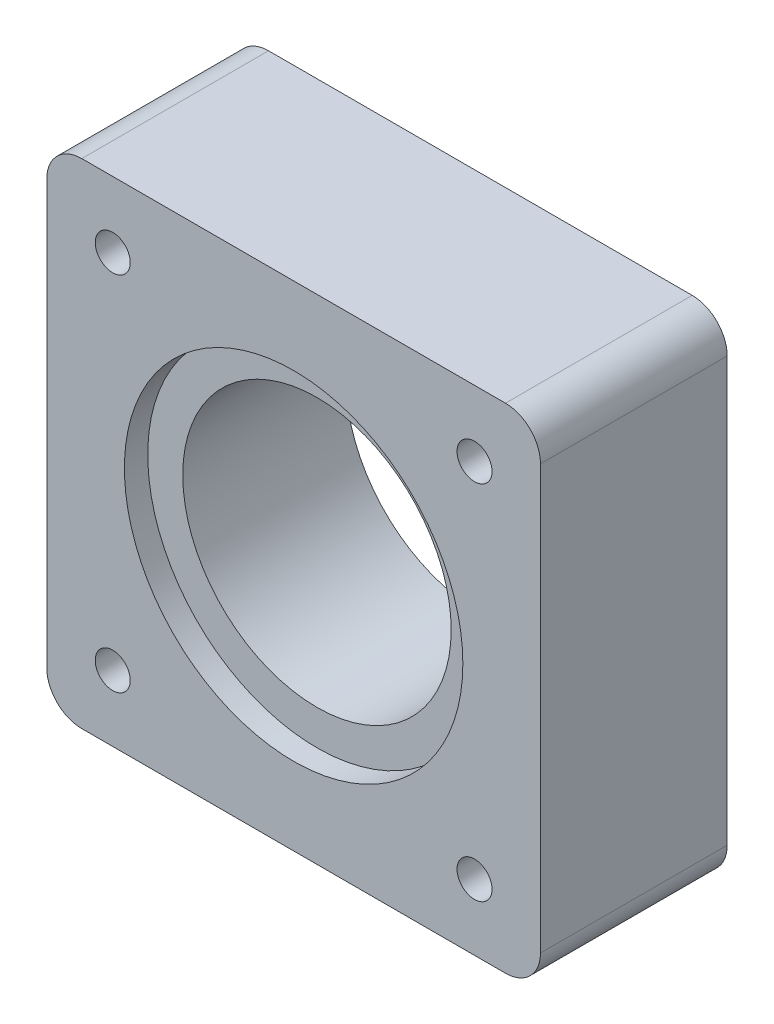
SolidWorks part; units mm, degrees
ref_plane "Plan de face" through (0, 0, 0) normal (0, 0, 1) x (1, 0, 0)
ref_plane "Plan de dessus" through (0, 0, 0) normal (0, 1, 0) x (1, 0, 0)
ref_plane "Plan de droite" through (0, 0, 0) normal (1, 0, 0) x (0, 0, -1)
sketch "Esquisse1" plane through (0, 0, 0) normal (0, 0, 1) x (1, 0, 0)
  line L1 (0, 0) -> (42.3, 0)
  line L2 (0, 0) -> (0, 42.3)
  line L3 (0, 42.3) -> (42.3, 42.3)
  line L4 (42.3, 0) -> (42.3, 42.3)
  dimension "D1" = 42.3
  dimension "D2" = 42.3
extrude "Boss.-Extru.1" add sketch "Esquisse1" along normal blind 16
sketch "Esquisse2" plane through (0, 0, 0) normal (0, 0, 1) x (1, 0, 0)
  line L0 (42.3, 0) -> (42.3, 42.3) construction
  line L2 (42.3, 42.3) -> (0, 42.3) construction
  line L3 (0, 42.3) -> (0, 0) construction
  line L5 (0, 0) -> (42.3, 0) construction
  circle A0 centre (36.65, 36.65) radius 1.5
  circle A1 centre (5.65, 36.65) radius 1.5
  circle A2 centre (5.65, 5.65) radius 1.5
  circle A3 centre (36.65, 5.65) radius 1.5
  dimension "D1" = 3
  dimension "D2" = 3
  dimension "D3" = 3
  dimension "D4" = 3
  dimension "D9" = 5.65
  dimension "D5" = 5.65
  dimension "D6" = 5.65
  dimension "D7" = 5.65
  dimension "D8" = 5.65
  dimension "D10" = 5.65
  dimension "D11" = 5.65
  dimension "D12" = 5.65
extrude "Enlèv. mat.-Extru.2" cut sketch "Esquisse2" along normal through all
fillet "Congé1" radius 3 2 edges at (0, 42.3, 8) (42.3, 42.3, 8)
fillet "Congé2" radius 3 2 edges at (42.3, 0, 8) (0, 0, 8)
sketch "Esquisse4" plane through (0, 0, 0) normal (0, 0, 1) x (1, 0, 0)
  line L0 (39.3, 42.3) -> (3, 42.3) construction
  line L1 (0, 39.3) -> (0, 3) construction
  circle A0 centre (21.15, 21.15) radius 11.5
  point P6 (21.15, 42.3)
  dimension "D1" = 23
  dimension "D2" = 21.15
  dimension "D3" = 21.15
extrude "Enlèv. mat.-Extru.4" cut sketch "Esquisse4" along normal through all
sketch "Esquisse5" plane through (0, 0, 0) normal (0, 0, 1) x (1, 0, 0)
  circle A0 centre (36.65, 36.65) radius 2.85
  circle A1 centre (5.65, 36.65) radius 2.85
  circle A2 centre (5.65, 5.65) radius 2.85
  circle A3 centre (36.65, 5.65) radius 2.85
  dimension "D1" = 5.7
  dimension "D2" = 5.7
  dimension "D3" = 5.7
  dimension "D4" = 5.7
extrude "Enlèv. mat.-Extru.5" cut sketch "Esquisse5" along normal blind 10
sketch "Esquisse6" plane through (0, 0, 0) normal (0, 0, 1) x (1, 0, 0)
  line L0 (3, 0) -> (39.3, 0) construction
  line L1 (0, 39.3) -> (0, 3) construction
  line L2 (42.3, 3) -> (42.3, 39.3) construction
  circle A0 centre (29.3, 6.5) radius 4.35
  circle A1 centre (13, 6.5) radius 4.35
  dimension "D1" = 8.7
  dimension "D2" = 8.7
  dimension "D4" = 6.5
  dimension "D5" = 13
  dimension "D6" = 13
  dimension "D3" = 6.5
extrude "Enlèv. mat.-Extru.6" cut sketch "Esquisse6" along normal blind 12
sketch "Esquisse7" plane through (0, 0, 16) normal (0, 0, 1) x (1, 0, 0)
  circle A0 centre (21.15, 21.15) radius 14.5
  circle A1 centre (21.15, 21.15) radius 11.5 construction
  dimension "D1" = 0
  dimension "D2" = 29
extrude "Enlèv. mat.-Extru.7" cut sketch "Esquisse7" against normal blind 2
